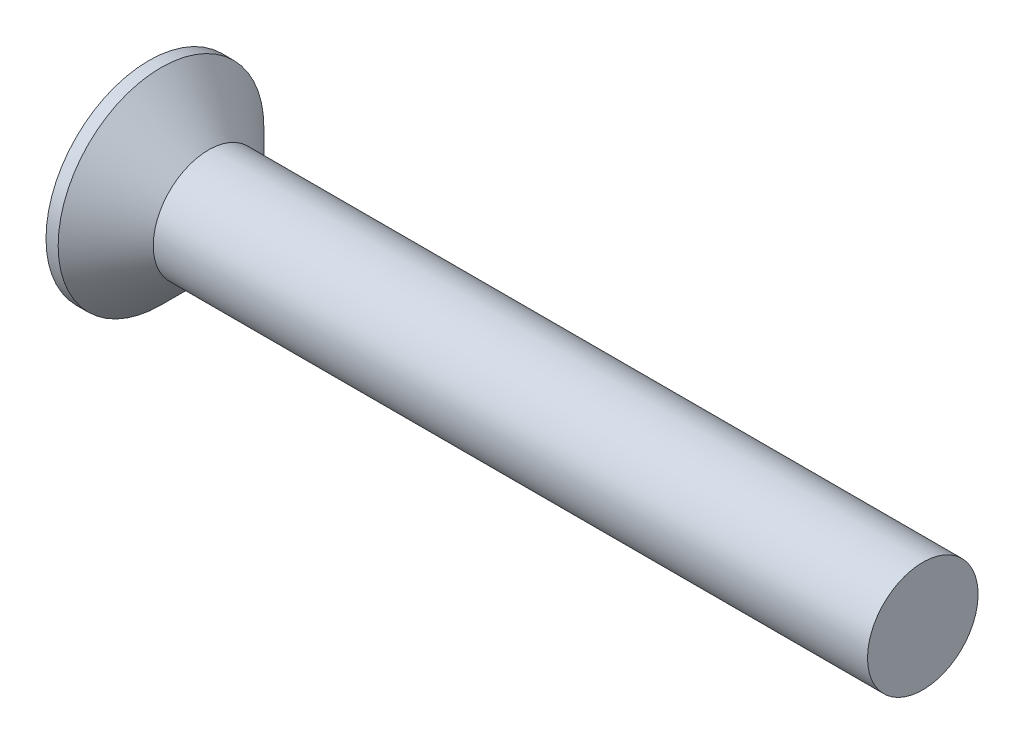
SolidWorks part; units mm, degrees
ref_plane "Plan de face" through (0, 0, 0) normal (0, 0, 1) x (1, 0, 0)
ref_plane "Plan de dessus" through (0, 0, 0) normal (0, 1, 0) x (1, 0, 0)
ref_plane "Plan de droite" through (0, 0, 0) normal (1, 0, 0) x (0, 0, -1)
sketch "Esquisse1" plane through (0, 0, 0) normal (0, 0, 1) x (1, 0, 0)
  line L0 (0, 0) -> (35, 0)
  line L1 (35, 0) -> (35, 2.5)
  line L2 (35, 2.5) -> (2.7, 2.5)
  line L4 (0, 4.65) -> (0, 0)
  line L5 (0, 4.65) -> (0.55, 4.65)
  line L6 (0.55, 4.65) -> (2.7, 2.5)
  dimension "D1" = 35
  dimension "D2" = 2.5
  dimension "D3" = 4.65
  dimension "D4" = 2.7
  dimension "D5" = 45
revolve "Révolution1" add sketch "Esquisse1" angle 360 about L0
equation "\"D3@Esquisse1\"=9.3/2"
